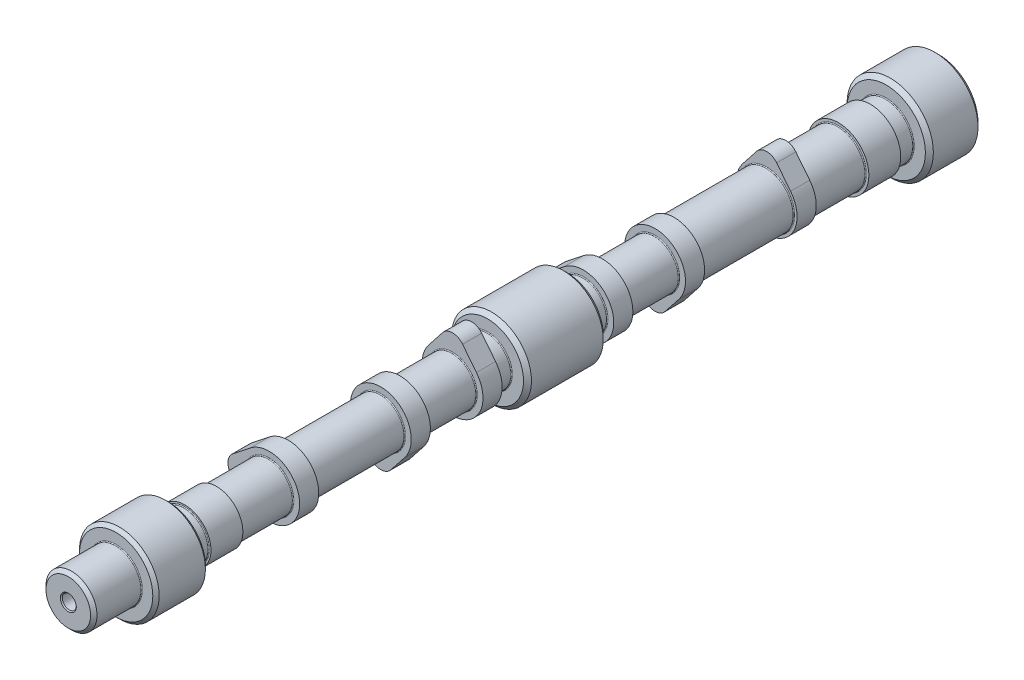
SolidWorks part; units mm, degrees
ref_plane "Front Plane" through (0, 0, 0) normal (0, 0, 1) x (1, 0, 0)
ref_plane "Top Plane" through (0, 0, 0) normal (0, 1, 0) x (1, 0, 0)
ref_plane "Right Plane" through (0, 0, 0) normal (1, 0, 0) x (0, 0, -1)
sketch "Sketch1" plane through (0, 0, 0) normal (1, 0, 0) x (0, 0, -1)
  line L0 (0, 0) -> (0, 14)
  line L1 (2, 16) -> (29.5, 16)
  line L2 (30, 16.5) -> (30, 23)
  line L3 (32, 25) -> (61, 25)
  line L4 (63, 23) -> (63, 15.5)
  line L5 (63.5, 15) -> (72.5, 15)
  line L6 (73, 15.5) -> (73, 16.5)
  line L7 (73, 16.5) -> (93, 16.5)
  line L8 (93, 16.5) -> (93, 15.5)
  line L9 (93.5, 15) -> (125.5, 15)
  line L10 (126, 15.5) -> (126, 17.0516)
  line L11 (126, 17.0516) -> (138, 17.0516)
  line L12 (0, 0) -> (546.0038, 0)
  line L13 (138, 17.0516) -> (138, 15.5)
  line L14 (138.5, 15) -> (195.5, 15)
  line L15 (196, 15.5) -> (196, 17.0516)
  line L16 (196, 17.0516) -> (208, 17.0516)
  line L17 (208, 17.0516) -> (208, 15.5)
  line L18 (208.5, 15) -> (240.5, 15)
  line L19 (241, 15.5) -> (241, 17.0516)
  line L20 (241, 17.0516) -> (253, 17.0516)
  line L21 (253, 17.0516) -> (253, 15.5)
  line L22 (253.5, 15) -> (262.5, 15)
  line L23 (263, 15.5) -> (263, 22.5)
  line L24 (265.5, 25) -> (310.5, 25)
  line L25 (313, 22.5) -> (313, 15.5)
  line L26 (313.5, 15) -> (322.5, 15)
  line L27 (323, 15.5) -> (323, 17.0516)
  line L28 (323, 17.0516) -> (335, 17.0516)
  line L29 (335, 17.0516) -> (335, 15.5)
  line L30 (335.5, 15) -> (367.5005, 15)
  line L31 (368.0005, 15.4995) -> (368.0038, 19.0917)
  line L32 (368.0038, 19.0917) -> (380.0038, 19.0917)
  line L33 (380.0038, 19.0917) -> (380.0038, 17.5401)
  line L34 (380.5038, 17.0401) -> (437.5038, 17.0401)
  line L35 (438.0038, 17.5401) -> (438.0038, 19.0917)
  line L36 (438.0038, 19.0917) -> (450.0038, 19.0917)
  line L37 (450.0038, 19.0917) -> (450.0038, 17.5401)
  line L38 (450.5038, 17.0401) -> (482.5038, 17.0401)
  line L39 (483.0038, 17.5401) -> (483.0038, 19.0917)
  line L40 (483.0038, 19.0917) -> (503.0038, 19.0917)
  line L41 (503.0038, 19.0917) -> (503.0038, 17.5401)
  line L42 (503.5038, 17.0401) -> (512.5038, 17.0401)
  line L43 (513.0038, 17.5401) -> (513.0038, 24.5401)
  line L44 (515.5038, 27.0401) -> (543.5038, 27.0401)
  line L45 (546.0038, 24.5401) -> (546.0038, 0)
  line L46 (0, 14) -> (2, 16)
  line L47 (30, 23) -> (32, 25)
  line L48 (61, 25) -> (63, 23)
  line L49 (263, 22.5) -> (265.5, 25)
  line L50 (310.5, 25) -> (313, 22.5)
  line L51 (513.0038, 24.5401) -> (515.5038, 27.0401)
  line L52 (543.5038, 27.0401) -> (546.0038, 24.5401)
  arc A0 (512.5038, 17.0401) -> (513.0038, 17.5401) centre (512.5038, 17.5401) ccw
  arc A1 (503.0038, 17.5401) -> (503.5038, 17.0401) centre (503.5038, 17.5401) ccw
  arc A2 (482.5038, 17.0401) -> (483.0038, 17.5401) centre (482.5038, 17.5401) ccw
  arc A3 (450.0038, 17.5401) -> (450.5038, 17.0401) centre (450.5038, 17.5401) ccw
  arc A4 (437.5038, 17.0401) -> (438.0038, 17.5401) centre (437.5038, 17.5401) ccw
  arc A5 (380.0038, 17.5401) -> (380.5038, 17.0401) centre (380.5038, 17.5401) ccw
  arc A6 (367.5005, 15) -> (368.0005, 15.4995) centre (367.5005, 15.5) ccw
  arc A7 (335, 15.5) -> (335.5, 15) centre (335.5, 15.5) ccw
  arc A8 (322.5, 15) -> (323, 15.5) centre (322.5, 15.5) ccw
  arc A9 (313, 15.5) -> (313.5, 15) centre (313.5, 15.5) ccw
  arc A10 (262.5, 15) -> (263, 15.5) centre (262.5, 15.5) ccw
  arc A11 (253.5, 15) -> (253, 15.5) centre (253.5, 15.5) cw
  arc A12 (240.5, 15) -> (241, 15.5) centre (240.5, 15.5) ccw
  arc A13 (208, 15.5) -> (208.5, 15) centre (208.5, 15.5) ccw
  arc A14 (195.5, 15) -> (196, 15.5) centre (195.5, 15.5) ccw
  arc A15 (138, 15.5) -> (138.5, 15) centre (138.5, 15.5) ccw
  arc A16 (125.5, 15) -> (126, 15.5) centre (125.5, 15.5) ccw
  arc A17 (93, 15.5) -> (93.5, 15) centre (93.5, 15.5) ccw
  arc A18 (72.5, 15) -> (73, 15.5) centre (72.5, 15.5) ccw
  arc A19 (63, 15.5) -> (63.5, 15) centre (63.5, 15.5) ccw
  arc A20 (29.5, 16) -> (30, 16.5) centre (29.5, 16.5) ccw
  point P1 (0, 16)
  point P3 (263, 25)
  point P5 (30, 25)
  point P6 (63, 25)
  point P26 (0, 0)
  point P27 (313, 25)
  point P46 (513.0038, 27.0401)
  point P47 (546.0038, 27.0401)
  point P49 (543.8076, -2.0401)
  point P51 (0, 0)
  point P66 (513.0038, 17.0401)
  point P69 (503.0038, 17.0401)
  point P72 (483.0038, 17.0401)
  point P75 (450.0038, 17.0401)
  point P78 (438.0038, 17.0401)
  point P81 (380.0038, 17.0401)
  point P84 (368, 15)
  point P87 (335, 15)
  point P90 (323, 15)
  point P93 (313, 15)
  point P96 (263, 15)
  point P99 (253, 15)
  point P102 (241, 15)
  point P105 (208, 15)
  point P108 (196, 15)
  point P111 (138, 15)
  point P114 (126, 15)
  point P117 (93, 15)
  point P120 (73, 15)
  point P123 (63, 15)
  point P126 (30, 16)
  dimension "D29" = 0.5
  dimension "D1" = 16
  dimension "D2" = 30
  dimension "D3" = 9
  dimension "D4" = 33
  dimension "D5" = 10
  dimension "D6" = 10
  dimension "D7" = 20
  dimension "D8" = 33
  dimension "D9" = 12
  dimension "D10" = 16.5
  dimension "D11" = 58
  dimension "D12" = 12
  dimension "D13" = 33
  dimension "D14" = 12
  dimension "D15" = 10
  dimension "D16" = 10
  dimension "D17" = 50
  dimension "D18" = 10
  dimension "D19" = 12
  dimension "D20" = 33
  dimension "D21" = 12
  dimension "D22" = 58
  dimension "D23" = 12
  dimension "D24" = 33
  dimension "D25" = 20
  dimension "D26" = 10
  dimension "D27" = 10
  dimension "D28" = 33
revolve "Revolve1" add sketch "Sketch1" angle 360 about L12
hole_wizard "Ø12.0 (12) Diameter Hole1" positions "Sketch2" profile "Sketch4" hole size "Ø12.0" standard "DIN"
sketch "Sketch2" plane through (0, 0, -546.0038) normal (0, 0, -1) x (-1, 0, 0)
  point P0 (0, 0)
sketch "Sketch4" plane through (0, 0, -546.0038) normal (1, 0, 0) x (0, 1, 0)
  line L0 (0, 0) -> (0, 18.4641)
  line L1 (0, 18.4641) -> (6, 15)
  line L2 (6, 15) -> (6, 1.525)
  line L3 (6, 1.525) -> (7.525, 0)
  line L5 (7.525, 0) -> (0, 0)
  line L6 (-6, 1.525) -> (-7.525, 0) construction
  line L10 (0, 18.4641) -> (-6, 15) construction
  line L11 (0, -6.35) -> (0, 107.95) construction
  dimension "Hole Dia." = 12
  dimension "Hole Depth" = 15
  dimension "Near C'Sink Dia." = 15.05
  dimension "Near C'Sink Angle" = 90
  dimension "Drill Angle" = 120
hole_wizard "M10x1.25 Tapped Hole1" positions "Sketch5" profile "Sketch6" tap size "M10x1.25" standard "DIN"
sketch "Sketch5" plane through (0, 0, 0) normal (0, 0, 1) x (1, 0, 0)
  point P0 (0, 0)
sketch "Sketch6" plane through (0, 0, 0) normal (1, 0, 0) x (0, -1, 0)
  line L0 (0, 0) -> (0, 28.8938)
  line L1 (0, 28.8938) -> (4.4, 26.25)
  line L2 (4.4, 26.25) -> (4.4, 0.625)
  line L3 (4.4, 0.625) -> (5.025, 0)
  line L5 (5.025, 0) -> (0, 0)
  line L6 (-4.4, 0.625) -> (-5.025, 0) construction
  line L10 (0, 28.8938) -> (-4.4, 26.25) construction
  line L11 (0, -6.35) -> (0, 107.95) construction
  dimension "Tap Drill Dia." = 8.8
  dimension "Tap Drill Depth" = 26.25
  dimension "Near C'Sink Dia." = 10.05
  dimension "Near C'Sink Angle" = 90
  dimension "Drill Angle" = 118
cosmetic thread "Hole Thread1" parameters "D1"=20, "D2"=10
sketch "Sketch7" plane through (0, 0, 0) normal (1, 0, 0) x (0, 0, -1)
  line L0 (2.205, -16) -> (26.205, -16)
  line L1 (2, -16) -> (29.5, -16) construction
  arc A0 (26.205, -16) -> (2.205, -16) centre (14.205, -25) ccw
  point P1 (14.205, -10)
  point P6 (14.205, -16)
  dimension "D1" = 6
  dimension "D2" = 15
extrude "Cut-Extrude1" cut sketch "Sketch7" against normal mid plane 5
sketch "Sketch8" plane through (0, 0, -450.0038) normal (0, 0, -1) x (-1, 0, 0)
  line L0 (0, 58.1216) -> (0, -35.5528) construction
  line L3 (-6.2808, 22.8632) -> (-14.989, 11.8247)
  line L4 (6.2808, 22.8632) -> (14.989, 11.8247)
  arc A4 (-14.989, 11.8247) -> (14.989, 11.8247) centre (0, 0) ccw
  arc A5 (6.2808, 22.8632) -> (-6.2808, 22.8632) centre (0, 17.9083) ccw
  circle A6 centre (0, 0) radius 19.0917 construction
  dimension "D1" = 8
extrude "Boss-Extrude2" add sketch "Sketch8" against normal up to surface (12 mm away) up to face at (17.5401, 0, -438.0038)
sketch "Sketch9" plane through (0, 0, -380.0038) normal (0, 0, -1) x (-1, 0, 0)
  line L4 (6.2808, -22.8632) -> (14.989, -11.8247)
  line L5 (-14.989, -11.8247) -> (-6.2808, -22.8632)
  arc A4 (14.989, -11.8247) -> (-14.989, -11.8247) centre (0, 0) ccw
  arc A5 (-6.2808, -22.8632) -> (6.2808, -22.8632) centre (0, -17.9083) ccw
extrude "Boss-Extrude3" add sketch "Sketch9" against normal up to surface (12 mm away)
sketch "Sketch10" plane through (0, 0, -335) normal (0, 0, -1) x (-1, 0, 0)
  line L4 (22.8632, 6.2808) -> (11.8247, 14.989)
  line L5 (11.8247, -14.989) -> (22.8632, -6.2808)
  arc A4 (11.8247, 14.989) -> (11.8247, -14.989) centre (0, 0) ccw
  arc A5 (22.8632, -6.2808) -> (22.8632, 6.2808) centre (17.9083, 0) ccw
extrude "Boss-Extrude4" add sketch "Sketch10" against normal up to surface (12 mm away) up to face at (15.5, 0, -323)
sketch "Sketch11" plane through (0, 0, -253) normal (0, 0, -1) x (-1, 0, 0)
  line L2 (-6.2808, 22.8632) -> (-14.989, 11.8247)
  line L3 (14.989, 11.8247) -> (6.2808, 22.8632)
  line L4 (-6.2808, 22.8632) -> (-14.989, 11.8247)
  line L5 (14.989, 11.8247) -> (6.2808, 22.8632)
  arc A2 (-14.989, 11.8247) -> (14.989, 11.8247) centre (0, 0) ccw
  arc A3 (6.2808, 22.8632) -> (-6.2808, 22.8632) centre (0, 17.9083) ccw
  arc A4 (-14.989, 11.8247) -> (14.989, 11.8247) centre (0, 0) ccw
  arc A5 (6.2808, 22.8632) -> (-6.2808, 22.8632) centre (0, 17.9083) ccw
  dimension "D1" = 0
extrude "Boss-Extrude5" add sketch "Sketch11" against normal up to surface (12 mm away) up to face at (15.5, 0, -241)
sketch "Sketch12" plane through (0, 0, -208) normal (0, 0, -1) x (-1, 0, 0)
  line L2 (6.2808, -22.8632) -> (14.989, -11.8247)
  line L3 (-14.989, -11.8247) -> (-6.2808, -22.8632)
  line L4 (6.2808, -22.8632) -> (14.989, -11.8247)
  line L5 (-14.989, -11.8247) -> (-6.2808, -22.8632)
  arc A2 (14.989, -11.8247) -> (-14.989, -11.8247) centre (0, 0) ccw
  arc A3 (-6.2808, -22.8632) -> (6.2808, -22.8632) centre (0, -17.9083) ccw
  arc A4 (14.989, -11.8247) -> (-14.989, -11.8247) centre (0, 0) ccw
  arc A5 (-6.2808, -22.8632) -> (6.2808, -22.8632) centre (0, -17.9083) ccw
  dimension "D1" = 0
extrude "Boss-Extrude6" add sketch "Sketch12" against normal up to surface (12 mm away) up to face at (15.5, 0, -196)
sketch "Sketch13" plane through (0, 0, -138) normal (0, 0, -1) x (-1, 0, 0)
  line L2 (22.8632, 6.2808) -> (11.8247, 14.989)
  line L3 (11.8247, -14.989) -> (22.8632, -6.2808)
  line L4 (22.8632, 6.2808) -> (11.8247, 14.989)
  line L5 (11.8247, -14.989) -> (22.8632, -6.2808)
  arc A2 (11.8247, 14.989) -> (11.8247, -14.989) centre (0, 0) ccw
  arc A3 (22.8632, -6.2808) -> (22.8632, 6.2808) centre (17.9083, 0) ccw
  arc A4 (11.8247, 14.989) -> (11.8247, -14.989) centre (0, 0) ccw
  arc A5 (22.8632, -6.2808) -> (22.8632, 6.2808) centre (17.9083, 0) ccw
  dimension "D1" = 0
extrude "Boss-Extrude7" add sketch "Sketch13" against normal up to surface (12 mm away) up to face at (15.5, 0, -126)
